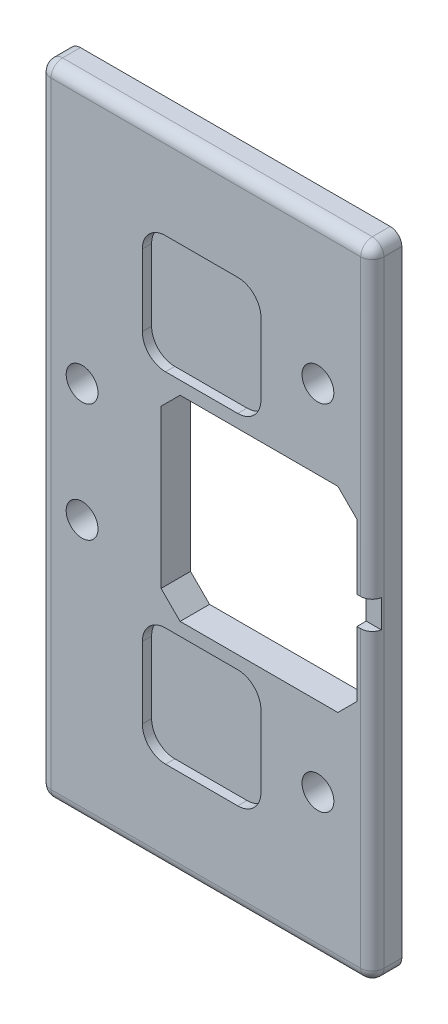
SolidWorks part; units mm, degrees
ref_plane "Front Plane" through (0, 0, 0) normal (0, 0, 1) x (1, 0, 0)
ref_plane "Top Plane" through (0, 0, 0) normal (0, 1, 0) x (1, 0, 0)
ref_plane "Right Plane" through (0, 0, 0) normal (1, 0, 0) x (0, 0, -1)
sketch "Sketch1" plane through (0, 0, 0) normal (0, 0, 1) x (1, 0, 0)
  line L0 (68.0566, 68.87) -> (126.0194, 68.87)
  line L22 (62.2146, 68.87) -> (68.0566, 68.87)
  line L28 (62.2146, -68.87) -> (126.0194, -68.87)
  line L31 (126.0194, -68.87) -> (126.0194, 68.87)
  line L38 (62.2146, 68.87) -> (54.2999, 68.87)
  line L40 (62.2146, -68.87) -> (54.2999, -68.87)
  line L41 (54.2999, 68.87) -> (54.2999, -68.87)
extrude "Boss-Extrude3" add sketch "Sketch1" along normal blind 6.35
ref_plane "Plane1" through (0, 0, 0) normal (0, -1, 0) x (-1, 0, 0)
sketch "Sketch6" plane through (0, 0, 0) normal (0, 0, -1) x (-1, 0, 0)
  circle A16 centre (-63.5, 12.7) radius 3.429
  circle A17 centre (-114.3, 38.1) radius 3.429
  circle A18 centre (-114.3, -38.1) radius 3.429
  circle A19 centre (-63.5, -12.7) radius 3.429
  point P0 (0, 0)
  dimension "D1" = 6.858
extrude "Cut-Extrude5" cut sketch "Sketch6" against normal up to surface (6.35 mm away) up to face at (90.1597, 0, 6.35)
fillet "Fillet2" radius 2.5 8 edges at (54.2999, 68.87, 3.175) (54.2999, -68.87, 3.175) (126.0194, -68.87, 3.175) (126.0194, 68.87, 3.175) (90.1597, 68.87, 6.35) (90.1597, -68.87, 6.35) (54.2999, 0, 6.35) (126.0194, 0, 6.35)
sketch "Sketch7" plane through (0, 0, 6.35) normal (0, 0, 1) x (1, 0, 0)
  line L0 (90.1597, -66.37) -> (90.1597, 66.37) construction
  line L3 (56.7999, -66.37) -> (123.5194, -66.37) construction
  line L5 (123.5194, 66.37) -> (56.7999, 66.37) construction
  line L6 (56.7999, 0) -> (123.5194, 0) construction
  line L7 (56.7999, 66.37) -> (56.7999, -66.37) construction
  line L8 (123.5194, -66.37) -> (123.5194, 66.37) construction
  circle A0 centre (90.1597, 0) radius 3.43
  dimension "D1" = 6.86
extrude "Cut-Extrude6" cut sketch "Sketch7" against normal through all
sketch "Sketch10" plane through (0, 0, 6.35) normal (0, 0, 1) x (1, 0, 0)
  line L0 (80.5121, 0) -> (56.7999, 0) construction
  line L14 (80.5121, 21.0947) -> (122.7015, 21.0947)
  line L15 (80.5121, 21.0947) -> (80.5121, -21.0947)
  line L16 (80.5121, -21.0947) -> (122.7015, -21.0947)
  line L17 (122.7015, 21.0947) -> (122.7015, -21.0947)
  line L18 (56.7999, 66.37) -> (56.7999, -66.37) construction
  dimension "D1" = 23.7122
extrude "Cut-Extrude8" cut sketch "Sketch10" against normal through all
sketch "Sketch11" plane through (0, 0, 6.35) normal (0, 0, 1) x (1, 0, 0)
  line L0 (123.5194, -66.37) -> (123.5194, 66.37) construction
  line L1 (123.5194, -3) -> (122.7015, -3)
  line L3 (123.5194, 3) -> (122.7015, 3)
  line L4 (122.7015, -3) -> (122.7015, 3)
  line L5 (122.7015, -21.0947) -> (122.7015, 21.0947) construction
  line L6 (123.1104, 3) -> (123.1104, 66.37) construction
  line L7 (123.5194, -3) -> (127.3985, -3)
  line L9 (123.5194, 3) -> (127.3985, 3)
  line L10 (127.3985, -3) -> (127.3985, 3)
  line L11 (123.5194, 66.37) -> (56.7999, 66.37) construction
  line L12 (123.1104, -3) -> (123.1104, -66.37) construction
  line L13 (56.7999, -66.37) -> (123.5194, -66.37) construction
  dimension "D1" = 6
extrude "Cut-Extrude9" cut sketch "Sketch11" against normal blind 2
sketch "Sketch12" plane through (0, 0, 6.35) normal (0, 0, 1) x (1, 0, 0)
  line L0 (76.4742, -44.3) -> (76.4742, -50.9707) construction
  line L1 (81.4742, -49.3) -> (76.4742, -49.3) construction
  line L2 (96.8742, -23.9) -> (102.0243, -23.9) construction
  line L3 (102.0243, -23.9) -> (101.8742, -28.9) construction
  line L5 (76.4742, -49.3) -> (102.0243, -49.3)
  line L6 (76.4742, -49.3) -> (76.4742, -23.9)
  line L7 (76.4742, -23.9) -> (102.0243, -23.9)
  line L8 (102.0243, -49.3) -> (102.0243, -23.9)
extrude "Cut-Extrude10" cut sketch "Sketch12" against normal blind 2
fillet "Fillet3" radius 5 4 edges at (102.0243, -23.9, 5.35) (76.4742, -23.9, 5.35) (76.4742, -49.3, 5.35) (102.0243, -49.3, 5.35)
mirror "Mirror1" about plane through (0, 0, 0) normal (0, -1, 0) of "Fillet3", "Cut-Extrude10"
chamfer "Chamfer1" distance 4.1 angle 45 4 edges at (80.5121, -21.0947, 3.175) (80.5121, 21.0947, 3.175) (122.7015, 21.0947, 3.175) (122.7015, -21.0947, 3.175)
